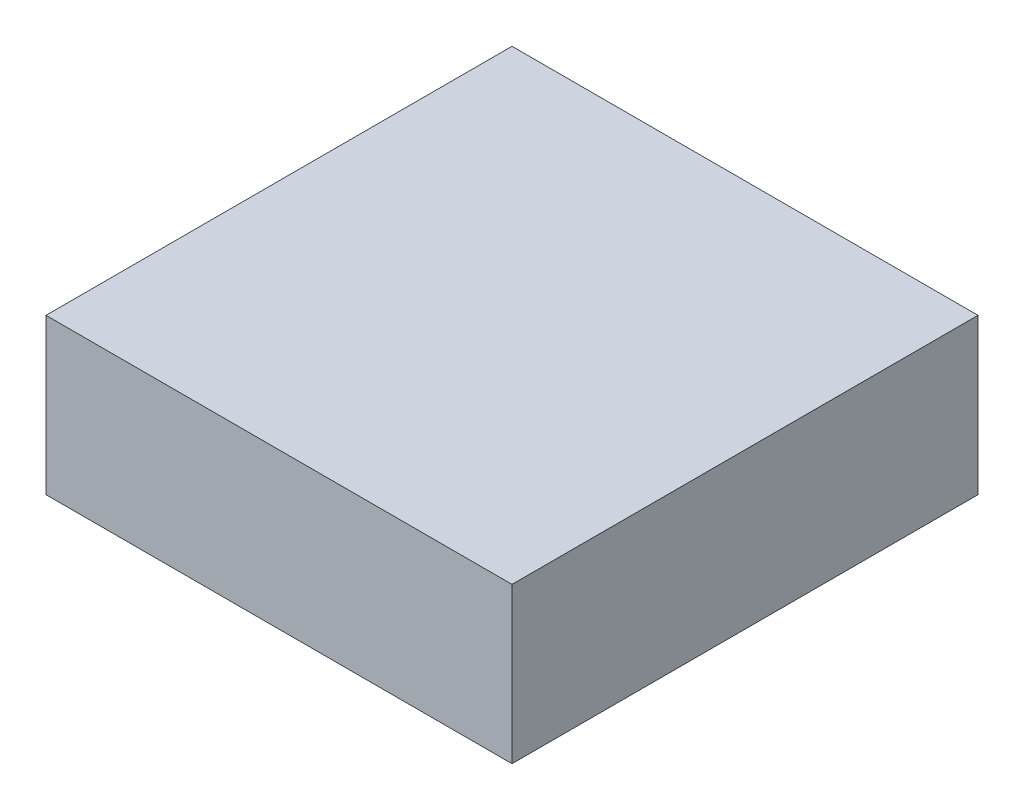
SolidWorks part; units mm, degrees
ref_plane "前视基准面" through (0, 0, 0) normal (0, 0, 1) x (1, 0, 0)
ref_plane "上视基准面" through (0, 0, 0) normal (0, 1, 0) x (1, 0, 0)
ref_plane "右视基准面" through (0, 0, 0) normal (1, 0, 0) x (0, 0, -1)
sketch "草图1" plane through (0, 0, 0) normal (0, 1, 0) x (1, 0, 0)
  line L1 (-600, -600) -> (600, -600)
  line L2 (-600, -600) -> (-600, 600)
  line L3 (-600, 600) -> (600, 600)
  line L4 (600, -600) -> (600, 600)
  line L5 (-600, -600) -> (600, 600) construction
  line L6 (-600, 600) -> (600, -600) construction
  point P0 (0, 0)
  dimension "D1" = 1200
  dimension "D2" = 1200
extrude "凸台-拉伸1" add sketch "草图1" along normal blind 400
sketch "草图2" plane through (0, 400, 0) normal (0, 1, 0) x (1, 0, 0)
  line L1 (-175, -175) -> (175, -175)
  line L2 (-175, -175) -> (-175, 175)
  line L3 (-175, 175) -> (175, 175)
  line L4 (175, -175) -> (175, 175)
  line L5 (-175, -175) -> (175, 175) construction
  line L6 (-175, 175) -> (175, -175) construction
  point P0 (0, 0)
  dimension "D1" = 350
  dimension "D2" = 350
